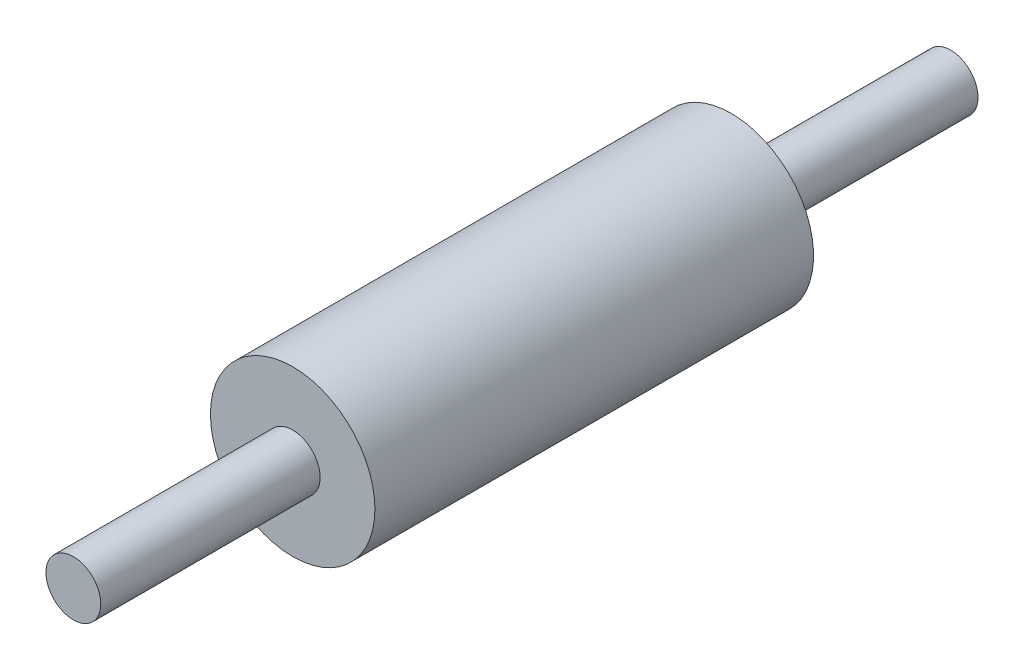
SolidWorks part; units mm, degrees
ref_plane "Alzado" through (0, 0, 0) normal (0, 0, 1) x (1, 0, 0)
ref_plane "Planta" through (0, 0, 0) normal (0, 1, 0) x (1, 0, 0)
ref_plane "Vista lateral" through (0, 0, 0) normal (1, 0, 0) x (0, 0, -1)
sketch "Croquis1" plane through (0, 0, 0) normal (0, 0, 1) x (1, 0, 0)
  circle A0 centre (0, 0) radius 15
  dimension "D1" = 30
extrude "Saliente-Extruir1" add sketch "Croquis1" along normal blind 160
sketch "Croquis2" plane through (0, 0, 0) normal (0, 0, -1) x (-1, 0, 0)
  circle A0 centre (0, 0) radius 5
  dimension "D1" = 10
extrude "Cortar-Extruir-Lámina1" cut sketch "Croquis2" against normal blind 40 thin
sketch "Croquis3" plane through (0, 0, 160) normal (0, 0, 1) x (1, 0, 0)
  circle A0 centre (0, 0) radius 5
  dimension "D1" = 10
extrude "Cortar-Extruir-Lámina2" cut sketch "Croquis3" against normal blind 40 thin
